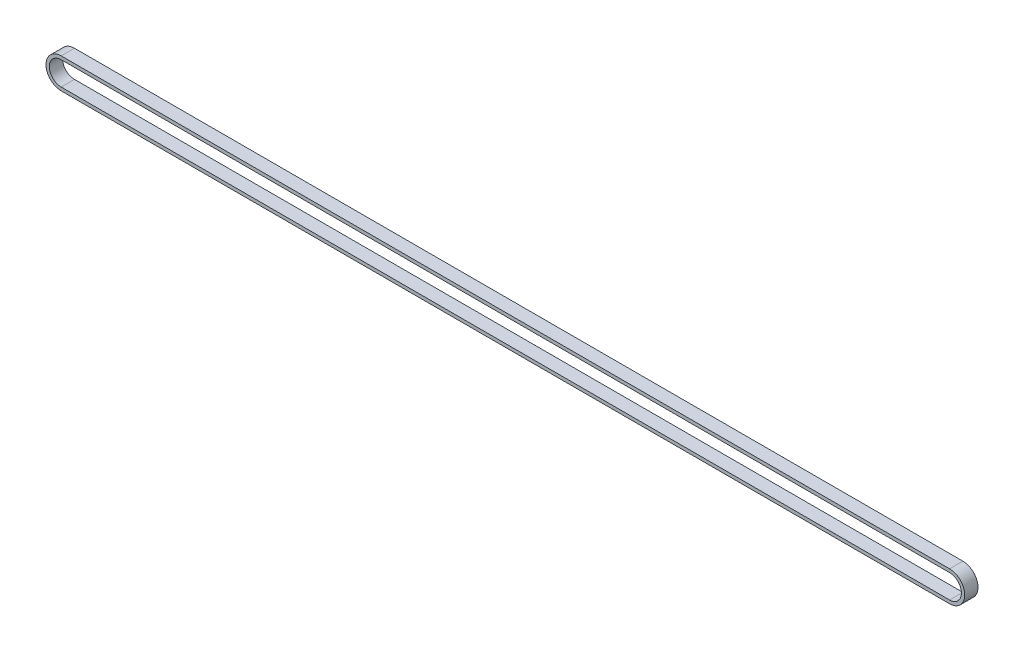
SolidWorks part; units mm, degrees
material "EPDM 60 Durometer"
ref_plane "Front" through (0, 0, 0) normal (0, 0, 1) x (1, 0, 0)
ref_plane "Top" through (0, 0, 0) normal (0, 1, 0) x (1, 0, 0)
ref_plane "Right" through (0, 0, 0) normal (1, 0, 0) x (0, 0, -1)
sketch "Sketch1" plane through (0, 0, 0) normal (0, 0, 1) x (1, 0, 0)
  line L0 (-200.8, 0) -> (200.8, 0) construction
  line L1 (-200.8, 6.85) -> (200.8, 6.85)
  line L2 (-200.8, -6.85) -> (200.8, -6.85)
  arc A0 (-200.8, 6.85) -> (-200.8, -6.85) centre (-200.8, 0) ccw
  arc A1 (200.8, -6.85) -> (200.8, 6.85) centre (200.8, 0) ccw
  point P2 (0, 0)
  dimension "D1" = 6.85
  dimension "D2" = 401.6
extrude "Extrude-Thin1" add sketch "Sketch1" along normal mid plane 6 thin contours L1 A1 L2 A0
